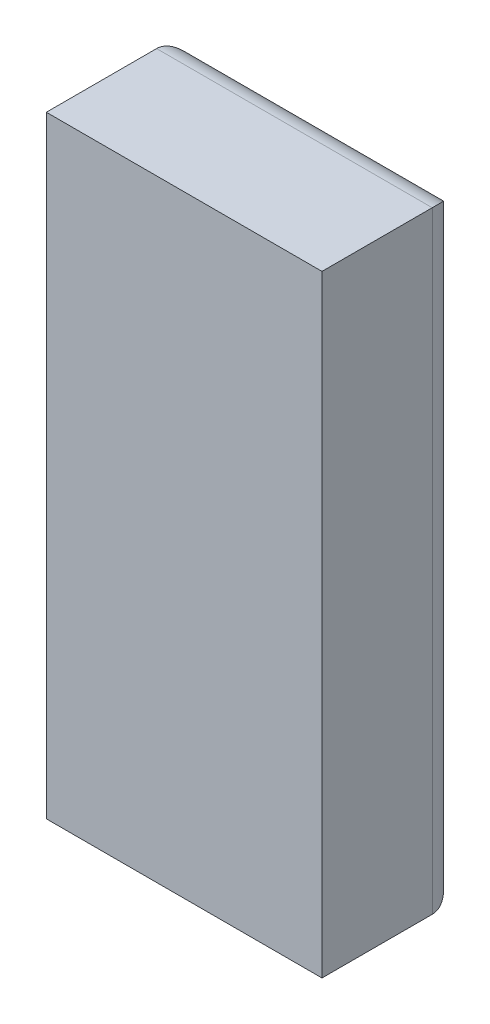
SolidWorks part; units mm, degrees
ref_plane "Front Plane" through (0, 0, 0) normal (0, 0, 1) x (1, 0, 0)
ref_plane "Top Plane" through (0, 0, 0) normal (0, 1, 0) x (1, 0, 0)
ref_plane "Right Plane" through (0, 0, 0) normal (1, 0, 0) x (0, 0, -1)
sketch "Profile Sketch" plane through (0, 0, 0) normal (0, 0, 1) x (1, 0, 0)
  line L1 (-50, 111) -> (50, 111)
  line L2 (-50, 111) -> (-50, -111)
  line L3 (-50, -111) -> (50, -111)
  line L4 (50, 111) -> (50, -111)
  line L5 (-50, 111) -> (50, -111) construction
  line L6 (-50, -111) -> (50, 111) construction
  point P0 (0, 0)
  dimension "D1" = 100
  dimension "D2" = 222
extrude "Profile Extrude" add sketch "Profile Sketch" against normal blind 50
fillet "Fillet1" radius 10 4 edges at (0, 111, -50) (-50, 0, -50) (0, -111, -50) (50, 0, -50)
